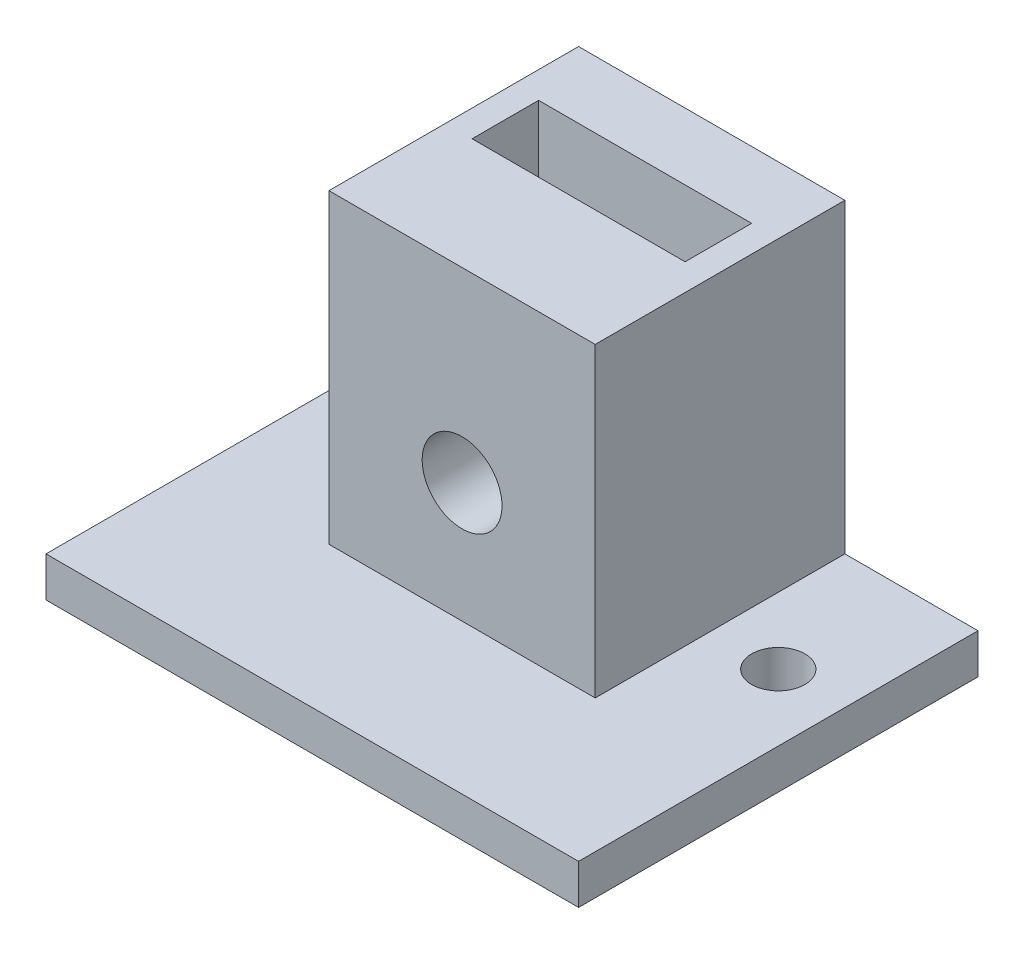
SolidWorks part; units mm, degrees
ref_plane "Plan de face" through (0, 0, 0) normal (0, 0, 1) x (1, 0, 0)
ref_plane "Plan de dessus" through (0, 0, 0) normal (0, 1, 0) x (1, 0, 0)
ref_plane "Plan de droite" through (0, 0, 0) normal (1, 0, 0) x (0, 0, -1)
sketch "Esquisse3" plane through (0, 0, 0) normal (0, 1, 0) x (1, 0, 0)
  line L0 (-0.0516, 15.6297) -> (-0.0516, -14.3703)
  line L1 (-20.0516, 15.6297) -> (19.9484, 15.6297)
  line L2 (-20.0516, 15.6297) -> (-20.0516, -14.3703)
  line L3 (-20.0516, -14.3703) -> (19.9484, -14.3703)
  line L4 (19.9484, 15.6297) -> (19.9484, -14.3703)
  line L5 (-20.0516, 0.6297) -> (19.9484, 0.6297)
  line L6 (19.9484, 15.6297) -> (19.9484, 5.6297)
  line L7 (19.9484, 5.6297) -> (-20.0516, 5.6297)
  line L8 (-0.0516, 5.6297) -> (-15.0516, 5.6297)
  line L9 (-15.0516, 5.6297) -> (14.9484, 5.6297)
  line L10 (-0.0516, 5.6297) -> (-10.0516, 5.6297)
  line L11 (-10.0516, 5.6297) -> (9.9484, 5.6297)
  line L12 (9.9484, 5.6297) -> (9.9484, -14.3703)
  line L13 (9.9484, -14.3703) -> (-10.0516, -14.3703)
  line L14 (-10.0516, -14.3703) -> (-10.0516, 5.6297)
  line L15 (-10.0516, 15.6297) -> (-10.0516, 5.6297)
  line L16 (9.9484, 5.6297) -> (9.9484, 15.6297)
  circle A0 centre (14.9484, 5.6297) radius 2
  circle A1 centre (-15.0516, 5.6297) radius 2
extrude "Boss.-Extru.1" add sketch "Esquisse3" along normal blind 3 contours L3 L14 L5 L2 | L5 L12 L3 L4 | A1 L9 L15 L1 L2 L7 | A1 L7 L2 L5 L14 L9 | L1 L15 L7 L0 | L9 L16 L1 L0 | A0 L7 L4 L1 L16 L9 | A0 L9 L12 L5 L4 L7 | L12 L5 L0 L3 | L14 L3 L0 L5 | L12 L9 L0 L5 | L14 L5 L0 L7
sketch "Esquisse4" plane through (0, 3, 0) normal (0, 1, 0) x (1, 0, 0)
  line L0 (-20.0516, 0.6297) -> (19.9484, 0.6297)
  line L1 (-20.0516, 15.6297) -> (-20.0516, -14.3703) construction
  line L2 (19.9484, 15.6297) -> (19.9484, -14.3703) construction
  line L3 (19.9484, 0.6297) -> (-0.0516, 15.6297)
  line L4 (-20.0516, 15.6297) -> (19.9484, 15.6297) construction
  line L5 (-0.0516, 15.6297) -> (-0.0516, -14.3703)
  line L6 (-20.0516, -14.3703) -> (19.9484, -14.3703) construction
  line L7 (-0.0516, -14.3703) -> (-20.0516, 0.6297)
  line L8 (-0.0516, 15.6297) -> (-20.0516, 0.6297)
  line L9 (-0.0516, -14.3703) -> (19.9484, 0.6297)
  line L10 (-15.0516, 5.6297) -> (14.9484, 5.6297)
  line L11 (14.9484, 5.6297) -> (14.9484, 15.6297)
  line L12 (-15.0516, 5.6297) -> (-15.0516, 15.6297)
  line L13 (-15.0516, 15.6297) -> (14.9484, 15.6297)
  line L14 (-0.0516, 5.6297) -> (-10.0516, 5.6297)
  line L15 (-0.0516, 5.6297) -> (9.9484, 5.6297)
  line L16 (-10.0516, 5.6297) -> (-10.0516, 15.6297)
  line L17 (-10.0516, 15.6297) -> (9.9484, 15.6297)
  line L18 (-15.0516, 5.6297) -> (-15.0516, -3.1203)
  line L19 (-15.0516, -3.1203) -> (14.9484, -3.1203)
  line L20 (14.9484, -3.1203) -> (14.9484, 5.6297)
  line L21 (-10.0516, 5.6297) -> (-10.0516, -3.1203)
  line L22 (9.9484, 5.6297) -> (9.9484, -3.1203)
  line L23 (9.9484, -3.1203) -> (9.9484, 15.6297)
  line M5 (19.9484, 15.6297) -> (-20.0516, 15.6297)
extrude "Boss.-Extru.2" add sketch "Esquisse4" along normal blind 17 contours L10 L21 L0 L5 | L0 L21 L19 L5 | L22 L0 L5 L19 | L22 L10 L5 L0 | L10 L23 L3 L5 | L16 L10 L5 L8 | L16 L8 M5 | L3 L23 L13
sketch "Esquisse5" plane through (0, 20, 0) normal (0, 1, 0) x (1, 0, 0)
  line L0 (-10.0516, 15.6297) -> (-10.0516, 10.6297)
  line L1 (-10.0516, 15.6297) -> (-10.0516, -3.1203) construction
  line L2 (-10.0516, 10.6297) -> (9.9484, 10.6297)
  line L3 (9.9484, 15.6297) -> (9.9484, -3.1203) construction
  line L4 (9.9484, 10.6297) -> (9.9484, 15.6297)
  line L5 (9.9484, 15.6297) -> (-10.0516, 15.6297)
  line L6 (9.9484, 10.6297) -> (-0.0516, 10.6297)
  line L7 (7.9484, 10.6297) -> (-8.0516, 10.6297)
  line L8 (7.9484, 10.6297) -> (7.9484, 5.6297)
  line L9 (-8.0516, 10.6297) -> (-8.0516, 5.6297)
  line L10 (7.9484, 5.6297) -> (-8.0516, 5.6297)
  point P13 (-0.0516, 10.6297)
ref_plane "Plan1" through (0, 0, -10.6297) normal (0, 0, -1) x (-1, 0, 0)
sketch "Esquisse6" plane through (0, 0, -10.6297) normal (0, 0, -1) x (-1, 0, 0)
  line L0 (-7.9484, 20) -> (8.0516, 20)
  line L2 (-7.9484, 12) -> (-7.9484, 20)
  line L5 (-7.9484, 20) -> (-7.9484, 4)
  line L6 (8.0516, 20) -> (8.0516, 4)
  line L11 (8.0516, 20) -> (-7.9484, 20)
  line L12 (8.0516, 20) -> (8.0516, 12)
  arc A1 (-7.9484, 12) -> (8.0516, 12) centre (0.0516, 12) ccw
extrude "Enlèv. mat.-Extru.1" cut sketch "Esquisse6" against normal blind 5 contours L2 A1 L6 L0
sketch "Esquisse7" plane through (0, 0, -15.6297) normal (0, 0, -1) x (-1, 0, 0)
  line L0 (8.0516, 20) -> (8.0516, 4)
  line L1 (-7.9484, 20) -> (8.0516, 20) construction
  line L2 (8.0516, 4) -> (-7.9484, 4)
  line L3 (-7.9484, 4) -> (-7.9484, 20)
  line L4 (-7.9484, 20) -> (8.0516, 20)
  line L5 (8.0516, 20) -> (-7.9484, 4)
  line L6 (8.0516, 4) -> (-7.9484, 20)
  circle A0 centre (0.0516, 12) radius 3
extrude "Enlèv. mat.-Extru.2" cut sketch "Esquisse7" against normal blind 18.75 contours L6 A0 L5 | L5 A0 L6 | L6 A0 L5 | L5 A0 L6
sketch "Esquisse8" plane through (0, 20, 0) normal (0, 1, 0) x (1, 0, 0)
  line L0 (-10.0516, 15.6297) -> (-10.0516, -3.1203)
  line L1 (-10.0516, -3.1203) -> (9.9484, -3.1203)
  line L2 (9.9484, 15.6297) -> (9.9484, -3.1203) construction
  line L3 (9.9484, 15.6297) -> (9.9484, -3.1203) construction
  line L4 (9.9484, -3.1203) -> (9.9484, 15.6297)
  line L5 (9.9484, 15.6297) -> (-10.0516, 15.6297)
  line L6 (-8.0516, 10.6297) -> (-8.0516, 5.6297)
  line L7 (-8.0516, 5.6297) -> (7.9484, 5.6297)
  line L8 (7.9484, 5.6297) -> (7.9484, 10.6297)
  line L9 (7.9484, 10.6297) -> (-8.0516, 10.6297)
extrude "Boss.-Extru.3" add sketch "Esquisse8" along normal blind 6 contours L5 L0 L1 L4 | L9 L6 L7 L8
